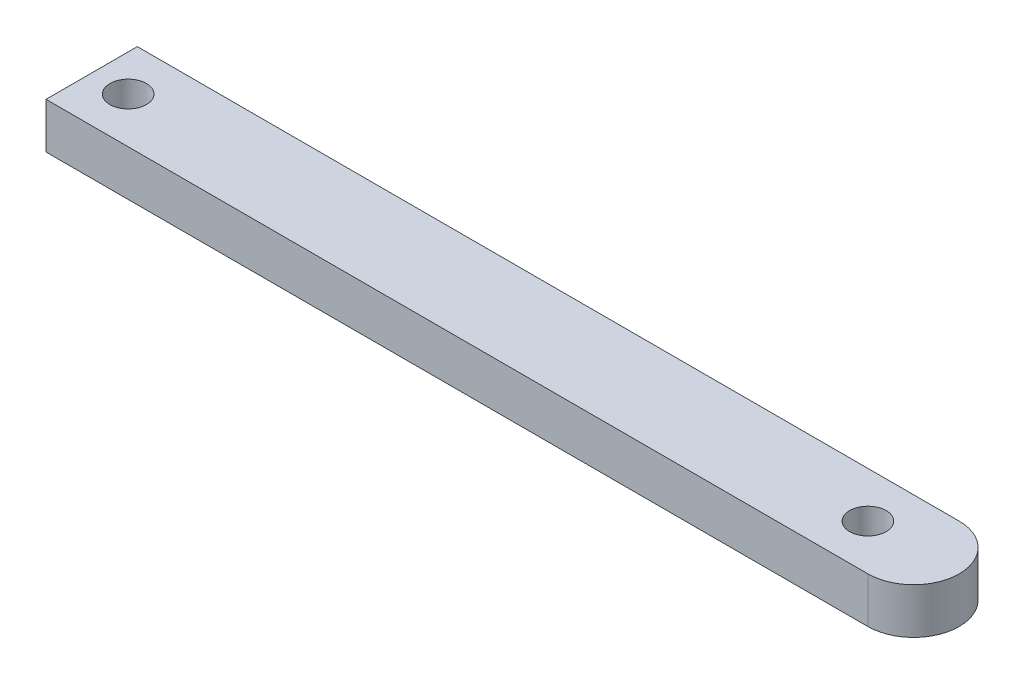
SolidWorks part; units mm, degrees
ref_plane "Front" through (0, 0, 0) normal (0, 0, 1) x (1, 0, 0)
ref_plane "Top" through (0, 0, 0) normal (0, 1, 0) x (1, 0, 0)
ref_plane "Right" through (0, 0, 0) normal (1, 0, 0) x (0, 0, -1)
sketch "Sketch1" plane through (0, 0, 0) normal (0, 1, 0) x (1, 0, 0)
  line L0 (90, 5) -> (80, 5) construction
  line L1 (0, 0) -> (80, 0)
  line L2 (0, 0) -> (0, 10)
  line L3 (0, 10) -> (80, 10)
  line L4 (80, 0) -> (80, 10)
  line L5 (90, 0) -> (80, 0)
  line L6 (90, 10) -> (80, 10)
  line L10 (0, 5) -> (4, 5)
  arc A0 (90, 0) -> (90, 10) centre (90, 5) ccw
  arc A1 (80, 10) -> (80, 0) centre (80, 5) ccw
  circle A4 centre (4, 5) radius 2
  circle A5 centre (12, 5) radius 2
  circle A6 centre (85, 5) radius 2
  point P7 (85, 5)
  dimension "D1" = 80
  dimension "D2" = 10
  dimension "D3" = 10
  dimension "D4" = 10
  dimension "D6" = 2
extrude "Boss-Extrude1" add sketch "Sketch1" along normal blind 5
